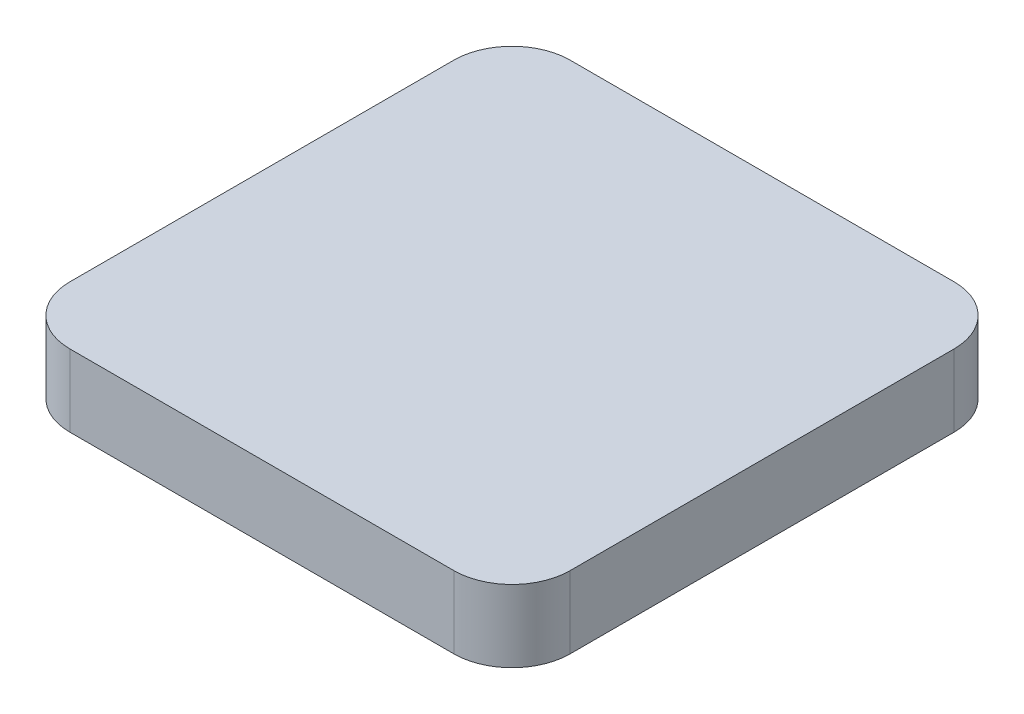
SolidWorks part; units mm, degrees
ref_plane "Front Plane" through (0, 0, 0) normal (0, 0, 1) x (1, 0, 0)
ref_plane "Top Plane" through (0, 0, 0) normal (0, 1, 0) x (1, 0, 0)
ref_plane "Right Plane" through (0, 0, 0) normal (1, 0, 0) x (0, 0, -1)
sketch "Sketch1" plane through (0, 0, 0) normal (0, 1, 0) x (1, 0, 0)
  line L1 (-4.191, 5.461) -> (4.191, 5.461)
  line L2 (-5.461, 4.191) -> (-5.461, -4.191)
  line L3 (-4.191, -5.461) -> (4.191, -5.461)
  line L4 (5.461, 4.191) -> (5.461, -4.191)
  line L5 (-5.461, 5.461) -> (5.461, -5.461) construction
  line L6 (-5.461, -5.461) -> (5.461, 5.461) construction
  arc A0 (-4.191, 5.461) -> (-5.461, 4.191) centre (-4.191, 4.191) ccw
  arc A1 (-4.191, -5.461) -> (-5.461, -4.191) centre (-4.191, -4.191) cw
  arc A2 (4.191, -5.461) -> (5.461, -4.191) centre (4.191, -4.191) ccw
  arc A3 (5.461, 4.191) -> (4.191, 5.461) centre (4.191, 4.191) ccw
  point P0 (0, 0)
  dimension "D3" = 1.27
  dimension "D1" = 10.922
  dimension "D2" = 10.922
extrude "Boss-Extrude1" add sketch "Sketch1" along normal blind 1.5748
